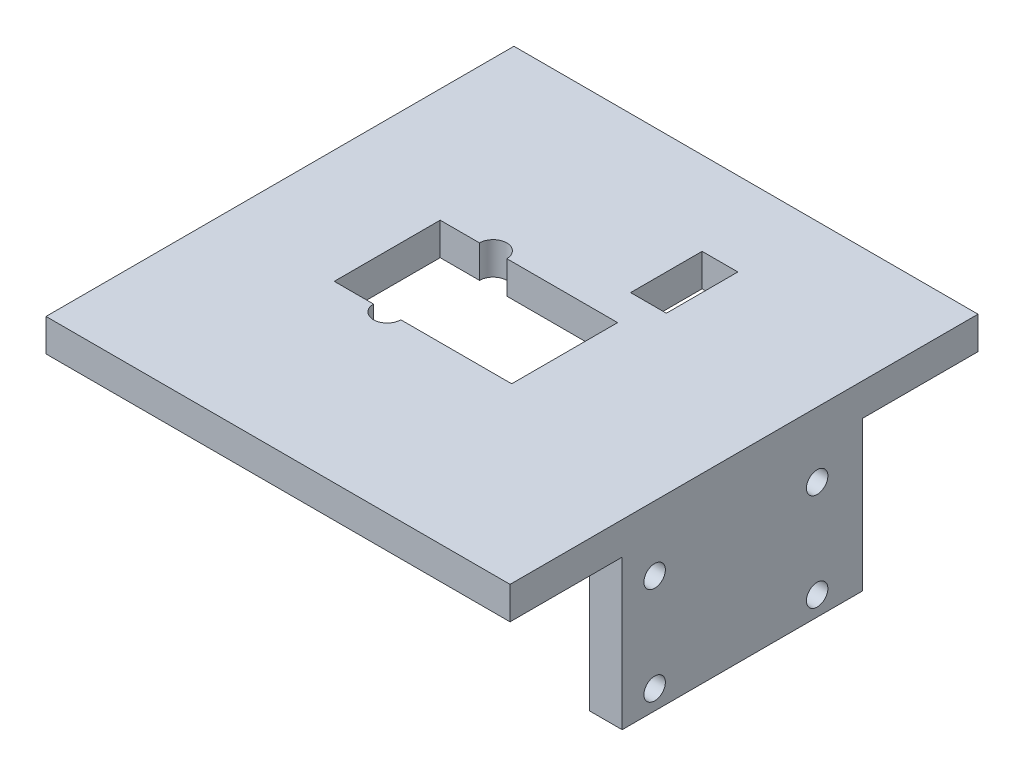
SolidWorks part; units mm, degrees
ref_plane "前视基准面" through (0, 0, 0) normal (0, 0, 1) x (1, 0, 0)
ref_plane "上视基准面" through (0, 0, 0) normal (0, 1, 0) x (1, 0, 0)
ref_plane "右视基准面" through (0, 0, 0) normal (1, 0, 0) x (0, 0, -1)
other "Configuration Table"
sketch "草图1" plane through (0, 0, 0) normal (0, 1, 0) x (1, 0, 0)
  line L1 (0, 0) -> (55, 0)
  line L2 (0, 0) -> (0, -70)
  line L3 (0, -70) -> (55, -70)
  line L4 (55, 0) -> (55, -70)
  dimension "D1" = 55
  dimension "D2" = 70
extrude "凸台-拉伸1" add sketch "草图1" along normal blind 5
sketch "草图2" plane through (55, 0, 0) normal (1, 0, 0) x (0, 0, -1)
  line L0 (0, 5) -> (0, 0) construction
  line L1 (0, 5) -> (-37, 5)
  line L2 (0, 5) -> (0, -23)
  line L3 (0, -23) -> (-37, -23)
  line L4 (-37, 5) -> (-37, -23)
  line L5 (-70, 5) -> (0, 5) construction
  dimension "D1" = 37
  dimension "D2" = 28
extrude "凸台-拉伸2" add sketch "草图2" against normal blind 5
sketch "草图3" plane through (55, 0, 0) normal (1, 0, 0) x (0, 0, -1)
  line L0 (-37, -23) -> (0, -23) construction
  line L2 (0, 5) -> (0, -23) construction
  circle A0 centre (-7, -5) radius 1.65
  circle A1 centre (-32, -5) radius 1.65
  circle A2 centre (-32, -20) radius 1.65
  circle A3 centre (-7, -20) radius 1.65
  dimension "D1" = 15
  dimension "D3" = 3.3
  dimension "D4" = 3.3
  dimension "D5" = 3.3
  dimension "D6" = 3.3
  dimension "D7" = 3
  dimension "D8" = 7
  dimension "D2" = 25
extrude "切除-拉伸1" cut sketch "草图3" against normal blind 5
sketch "草图4" plane through (0, 5, 0) normal (0, 1, 0) x (1, 0, 0)
  line L0 (55, 0) -> (0, 0) construction
  circle A0 centre (25.9415, -19.25) radius 3.6614
  dimension "D1" = 19.25
sketch "草图5" plane through (0, 5, 0) normal (0, 1, 0) x (1, 0, 0)
  line L1 (0, 0) -> (55, 0)
  line L2 (0, 0) -> (0, 15.75)
  line L3 (0, 15.75) -> (55, 15.75)
  line L4 (55, 0) -> (55, 15.75)
  circle A0 centre (25.9415, -19.25) radius 3.6614 construction
  dimension "D1" = 55
  dimension "D2" = 35
extrude "凸台-拉伸3" add sketch "草图5" against normal blind 5
sketch "草图6" plane through (0, 5, 0) normal (0, 1, 0) x (1, 0, 0)
  line L0 (0, 15.75) -> (0, -70) construction
  line L1 (0, -54.25) -> (55, -54.25)
  line L2 (0, -54.25) -> (0, -70)
  line L3 (0, -70) -> (55, -70)
  line L4 (55, -54.25) -> (55, -70)
  circle A0 centre (25.9415, -19.25) radius 3.6614 construction
  dimension "D1" = 35
extrude "切除-拉伸2" cut sketch "草图6" against normal blind 5
sketch "草图8" plane through (0, 5, 0) normal (0, 1, 0) x (1, 0, 0)
  line L0 (55, -54.25) -> (55, 15.75) construction
  line L2 (17.4, -11.1) -> (28.4, -11.1)
  line L3 (1.1, -27.4) -> (7.15, -27.4)
  line L4 (1.1, -27.4) -> (1.1, -11.1)
  line L5 (1.1, -11.1) -> (7.15, -11.1)
  line L7 (1.1, -27.4) -> (17.4, -11.1) construction
  line L8 (1.1, -11.1) -> (17.4, -27.4) construction
  line L9 (28.4, -11.1) -> (28.4, -27.4)
  line L10 (28.4, -27.4) -> (17.4, -27.4)
  line L11 (11.35, -11.1) -> (17.4, -11.1)
  line L12 (11.35, -27.4) -> (17.4, -27.4)
  arc A1 (7.15, -11.1) -> (11.35, -11.1) centre (9.25, -11.1) cw
  arc A2 (7.15, -27.4) -> (11.35, -27.4) centre (9.25, -27.4) ccw
  point P0 (9.25, -19.25)
  dimension "D1" = 45.75
  dimension "D6" = 2.1
  dimension "D3" = 16.3
  dimension "D4" = 16.3
  dimension "D5" = 11
extrude "切除-拉伸3" cut sketch "草图8" against normal blind 5
sketch "草图9" plane through (0, 5, 0) normal (0, 1, 0) x (1, 0, 0)
  line L0 (28.4, -11.1) -> (11.35, -11.1) construction
  line L1 (25.4, 4.9) -> (30.9, 4.9)
  line L2 (25.4, 4.9) -> (25.4, -6.1)
  line L3 (25.4, -6.1) -> (30.9, -6.1)
  line L4 (30.9, 4.9) -> (30.9, -6.1)
  line L5 (28.4, -27.4) -> (28.4, -11.1) construction
  dimension "D1" = 11
  dimension "D2" = 5
  dimension "D3" = 5.5
  dimension "D4" = 2.5
extrude "切除-拉伸4" cut sketch "草图9" against normal blind 8
sketch "草图10" plane through (0, 0, -15.75) normal (0, 0, -1) x (-1, 0, 0)
  line L0 (-55, 0) -> (0, 0) construction
  line L1 (-55, 0) -> (0, 0)
  line L2 (-55, 0) -> (-55, 10)
  line L3 (-55, 10) -> (0, 10)
  line L4 (0, 0) -> (0, 10)
  line L5 (-55, 0) -> (-55, 5) construction
  dimension "D1" = 10
  dimension "D2" = 55
sketch "草图11" plane through (0, 5, 0) normal (0, 1, 0) x (1, 0, 0)
  line L0 (1.1, -11.1) -> (1.1, -27.4) construction
  line L1 (0, 15.75) -> (-16.4, 15.75)
  line L2 (0, 15.75) -> (0, -54.25)
  line L3 (0, -54.25) -> (-16.4, -54.25)
  line L4 (-16.4, 15.75) -> (-16.4, -54.25)
  dimension "D1" = 17.5
extrude "凸台-拉伸4" add sketch "草图11" against normal blind 5
sketch "草图12" plane through (0, 5, 0) normal (0, 1, 0) x (1, 0, 0)
  line L0 (55, -54.25) -> (55, 15.75) construction
  line L1 (-16.4, 15.75) -> (55, 15.75)
  line L2 (-16.4, 15.75) -> (-16.4, 17.75)
  line L3 (-16.4, 17.75) -> (55, 17.75)
  line L4 (55, 15.75) -> (55, 17.75)
  dimension "D1" = 2
extrude "凸台-拉伸5" add sketch "草图12" against normal blind 5
